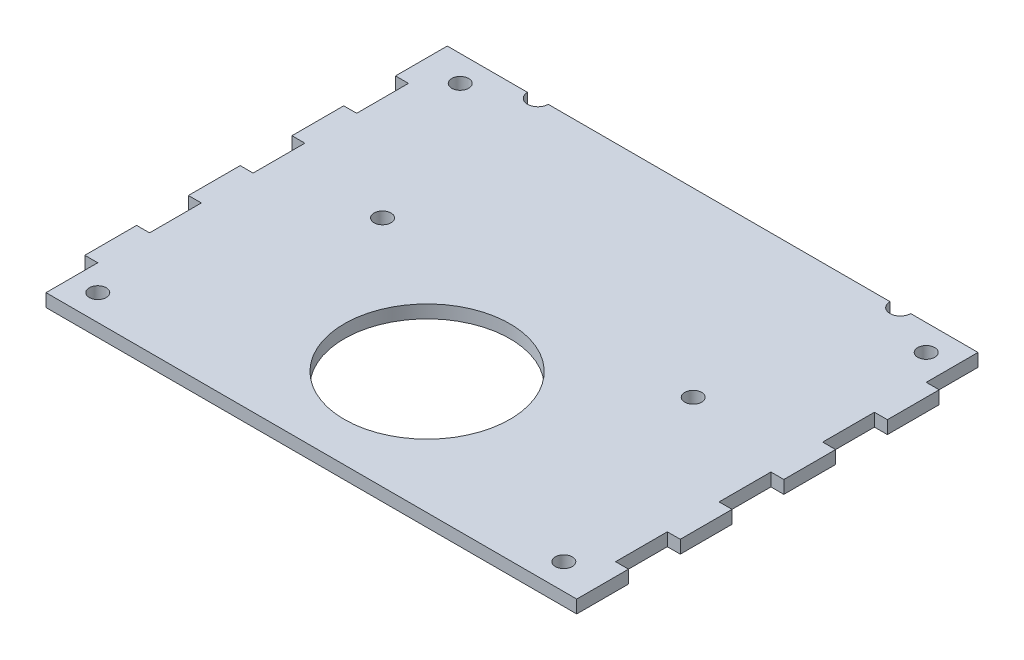
SolidWorks part; units mm, degrees
ref_plane "Front Plane" through (0, 0, 0) normal (0, 0, 1) x (1, 0, 0)
ref_plane "Top Plane" through (0, 0, 0) normal (0, 1, 0) x (1, 0, 0)
ref_plane "Right Plane" through (0, 0, 0) normal (1, 0, 0) x (0, 0, -1)
sketch "Sketch2" plane through (0, 0, 0) normal (0, 1, 0) x (1, 0, 0)
  line L0 (15.875, 0) -> (15.875, 12.7)
  line L1 (79.375, 127) -> (79.375, 0) construction
  line L2 (15.875, 12.7) -> (12.7, 12.7)
  line L3 (41.275, 57.15) -> (15.875, 57.15) construction
  line L4 (15.875, 50.8) -> (142.875, 50.8) construction
  line L5 (15.875, 50.8) -> (12.7, 50.8)
  line L6 (12.7, 25.4) -> (15.875, 25.4)
  line L7 (15.875, 38.1) -> (12.7, 38.1)
  line L8 (12.7, 76.2) -> (12.7, 63.5)
  line L9 (12.7, 50.8) -> (12.7, 38.1)
  line L10 (15.875, 25.4) -> (15.875, 38.1)
  line L11 (15.875, 63.5) -> (12.7, 63.5)
  line L12 (146.05, 88.9) -> (146.05, 76.2)
  line L13 (12.7, 76.2) -> (15.875, 76.2)
  line L14 (15.875, 50.8) -> (15.875, 63.5)
  line L15 (15.875, 88.9) -> (12.7, 88.9)
  line L16 (146.05, 12.7) -> (146.05, 0)
  line L17 (12.7, 101.6) -> (15.875, 101.6)
  line L18 (15.875, 76.2) -> (15.875, 88.9)
  line L19 (15.875, 95.25) -> (22.225, 95.25) construction
  line L20 (142.875, 95.25) -> (136.525, 95.25) construction
  line L21 (12.7, 101.6) -> (12.7, 88.9)
  line L22 (12.7, 25.4) -> (12.7, 12.7)
  line L23 (142.875, 6.35) -> (136.525, 6.35) construction
  line L24 (117.475, 57.15) -> (142.875, 57.15) construction
  line L25 (146.05, 38.1) -> (146.05, 25.4)
  line L26 (15.875, 101.6) -> (32.385, 101.6)
  line L27 (146.05, 12.7) -> (142.875, 12.7)
  line L28 (146.05, 63.5) -> (146.05, 50.8)
  line L29 (142.875, 12.7) -> (142.875, 25.4)
  line L30 (142.875, 25.4) -> (146.05, 25.4)
  line L31 (146.05, 38.1) -> (142.875, 38.1)
  line L32 (142.875, 38.1) -> (142.875, 50.8)
  line L33 (142.875, 50.8) -> (146.05, 50.8)
  line L34 (15.875, 101.6) -> (32.385, 101.6) construction
  line L35 (15.875, 44.45) -> (15.875, 50.8) construction
  line L36 (15.875, 44.45) -> (79.375, 44.45) construction
  line L37 (79.375, 44.45) -> (79.375, 29.972) construction
  line L38 (146.05, 63.5) -> (142.875, 63.5)
  line L39 (142.875, 63.5) -> (142.875, 76.2)
  line L40 (142.875, 76.2) -> (146.05, 76.2)
  line L41 (37.465, 101.6) -> (121.285, 101.6)
  line L42 (146.05, 88.9) -> (142.875, 88.9)
  line L43 (142.875, 88.9) -> (142.875, 101.6)
  line L44 (126.365, 101.6) -> (142.875, 101.6)
  line L53 (15.875, 0) -> (146.05, 0)
  line L54 (149.225, 44.45) -> (149.225, 50.8) construction
  line L55 (15.875, 6.35) -> (22.225, 6.35) construction
  line L77 (9.525, 152.4) -> (15.875, 152.4) [skipped]
  line L79 (15.875, 139.7) -> (9.525, 139.7) [skipped]
  line L80 (15.875, 114.3) -> (9.525, 114.3) [skipped]
  line L82 (9.525, 127) -> (15.875, 127) [skipped]
  line L83 (9.525, 50.8) -> (15.875, 50.8) [skipped]
  circle A0 centre (41.275, 57.15) radius 2.0828
  circle A1 centre (136.525, 6.35) radius 2.0828
  circle A2 centre (79.375, 29.972) radius 20.32
  circle A3 centre (22.225, 6.35) radius 2.0828
  circle A4 centre (117.475, 57.15) radius 2.0828
  circle A5 centre (22.225, 95.25) radius 2.0828
  circle A6 centre (136.525, 95.25) radius 2.0828
  arc A7 (32.385, 101.6) -> (37.465, 101.6) centre (34.925, 101.6) ccw
  arc A8 (126.365, 101.6) -> (121.285, 101.6) centre (123.825, 101.6) cw
  point P67 (0, 0)
  dimension "D1" = 63.5
  dimension "D5" = 25.4
  dimension "D2" = 6
  dimension "D4" = 19.05
  dimension "D8" = 40.64
  dimension "D3" = 29.972
  dimension "D6" = 6.35
  dimension "D7" = 19.05
extrude "Boss-Extrude1" add sketch "Sketch2" along normal blind 3.175
